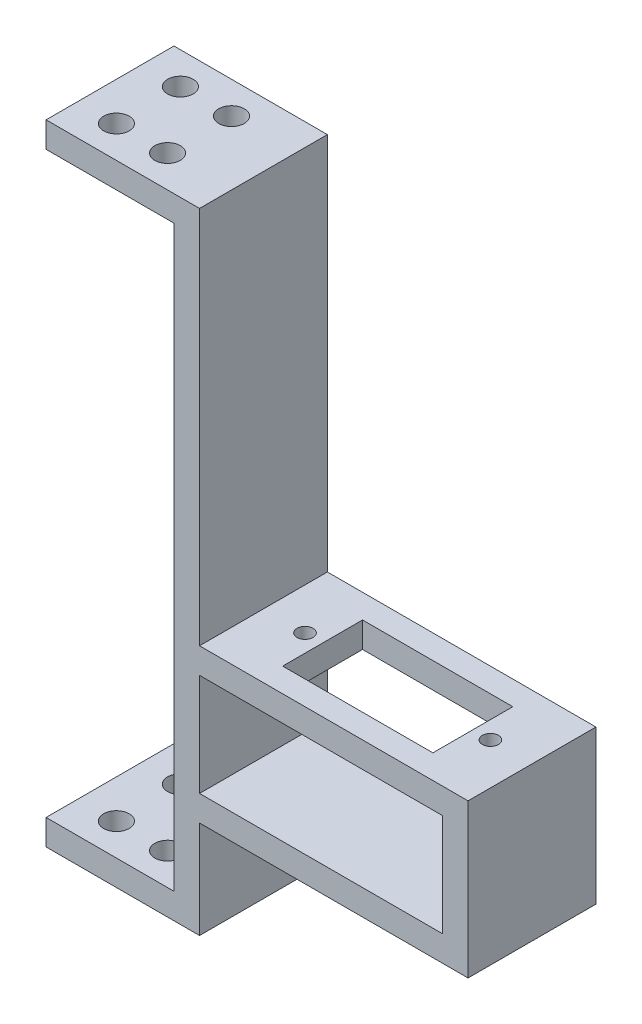
SolidWorks part; units mm, degrees
ref_plane "Front Plane" through (0, 0, 0) normal (0, 0, 1) x (1, 0, 0)
ref_plane "Top Plane" through (0, 0, 0) normal (0, 1, 0) x (1, 0, 0)
ref_plane "Right Plane" through (0, 0, 0) normal (1, 0, 0) x (0, 0, -1)
sketch "Sketch1" plane through (0, 0, 0) normal (0, 0, 1) x (1, 0, 0)
  line L0 (-24, 49.25) -> (0, 49.25)
  line L1 (0, 49.25) -> (0, -49.25)
  line L2 (0, -49.25) -> (-24, -49.25)
  line L3 (-24, 45.25) -> (-4, 45.25)
  line L4 (-4, 45.25) -> (-4, -45.25)
  line L5 (-4, -45.25) -> (-24, -45.25)
  line L6 (-24, 49.25) -> (-24, 45.25)
  line L7 (-24, -49.25) -> (-24, -45.25)
  point P9 (-12, -49.25)
  point P12 (0, 0)
  dimension "D2" = 98.5
  dimension "D3" = 20
  dimension "D1" = 4
extrude "Boss-Extrude1" add sketch "Sketch1" along normal mid plane 20
sketch "Sketch2" plane through (0, 0, 10) normal (0, 0, 1) x (1, 0, 0)
  line L0 (0, -14) -> (38, -14)
  line L1 (0, -49.25) -> (0, 49.25) construction
  line L2 (38, -14) -> (38, -30)
  line L3 (38, -30) -> (0, -30)
  line L5 (0, -10) -> (42, -10)
  line L6 (42, -10) -> (42, -34)
  line L7 (42, -34) -> (0, -34)
  line L8 (0, -14) -> (0, -10)
  line L9 (0, -30) -> (0, -34)
  dimension "D2" = 38
  dimension "D3" = 16
  dimension "D4" = 10
  dimension "D1" = 4
extrude "Boss-Extrude2" add sketch "Sketch2" against normal blind 20
sketch "Sketch3" plane through (0, -10, 0) normal (0, 1, 0) x (1, 0, 0)
  line L0 (42, -10) -> (0, -10) construction
  line L1 (9.25, 6.25) -> (32.75, 6.25)
  line L2 (9.25, 6.25) -> (9.25, -6.25)
  line L3 (9.25, -6.25) -> (32.75, -6.25)
  line L4 (32.75, 6.25) -> (32.75, -6.25)
  line L5 (42, 10) -> (42, -10) construction
  point P4 (21, -6.25)
  point P7 (21, -10)
  point P8 (32.75, 0)
  point P11 (42, 0)
  dimension "D1" = 23.5
  dimension "D2" = 12.5
extrude "Cut-Extrude1" cut sketch "Sketch3" against normal blind 5
sketch "Sketch4" plane through (0, -10, 0) normal (0, 1, 0) x (1, 0, 0)
  line L0 (6.5, 0) -> (35.5, 0) construction
  line L1 (42, 10) -> (0, 10) construction
  line L2 (9.25, 6.25) -> (9.25, -6.25) construction
  circle A0 centre (35.5, 0) radius 1.25
  circle A1 centre (6.5, 0) radius 1.25
  point P4 (21, 0)
  point P7 (21, 10)
  point P10 (9.25, 0)
  dimension "D1" = 2.5
  dimension "D2" = 29
extrude "Cut-Extrude2" cut sketch "Sketch4" against normal blind 5
sketch "Sketch5" plane through (0, 49.25, 0) normal (0, 1, 0) x (1, 0, 0)
  line L0 (-24, -10) -> (-24, 10) construction
  line L1 (-18, 5) -> (-10, 5)
  line L2 (-18, 5) -> (-18, -5)
  line L3 (-18, -5) -> (-10, -5)
  line L4 (-10, 5) -> (-10, -5)
  line L5 (-18, 5) -> (-10, -5) construction
  line L6 (-18, -5) -> (-10, 5) construction
  line L9 (-24, -10) -> (-4, -10) construction
  circle A0 centre (-18, 5) radius 2
  circle A1 centre (-18, -5) radius 2
  circle A2 centre (-10, -5) radius 2
  circle A3 centre (-10, 5) radius 2
  point P0 (-14, 0)
  point P5 (-18, 0)
  point P8 (-24, 0)
  point P13 (-14, -5)
  point P16 (-14, -10)
  dimension "D3" = 4
  dimension "D1" = 10
  dimension "D2" = 8
extrude "Cut-Extrude3" cut sketch "Sketch5" against normal through all contours A1 | A2 | A3 | A0
